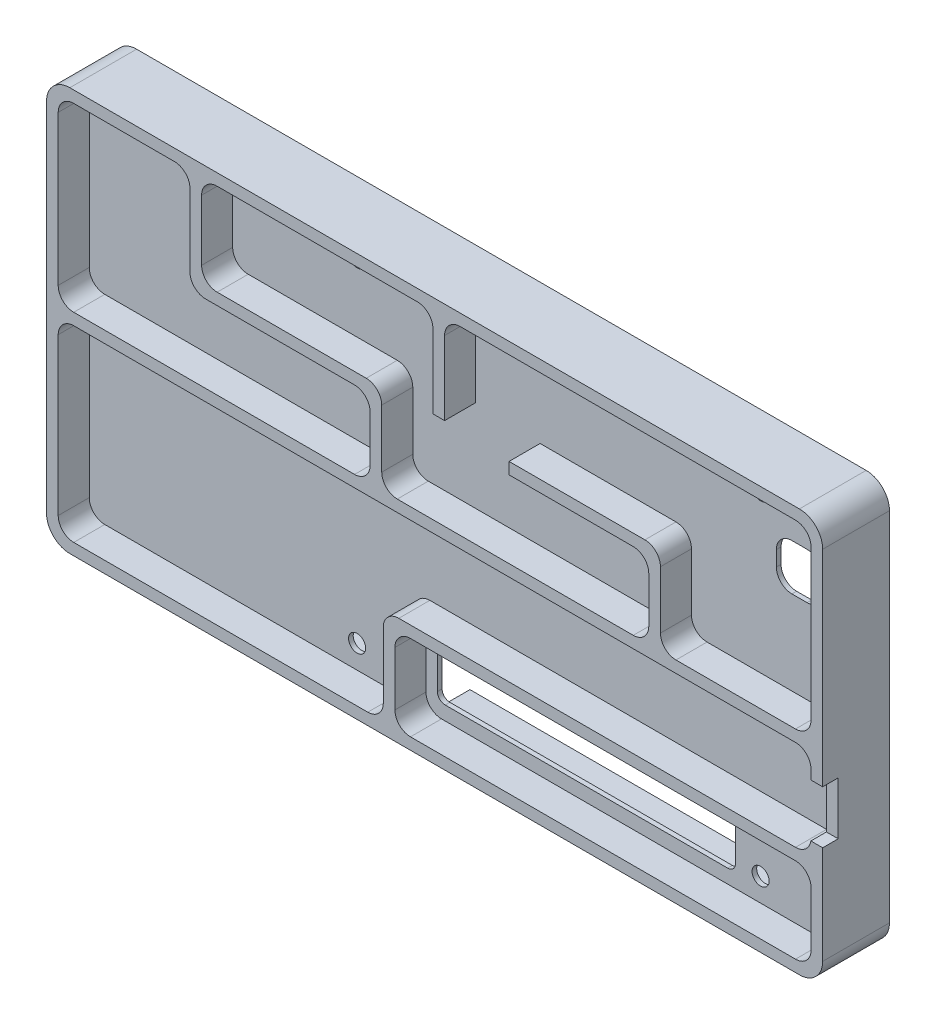
SolidWorks part; units mm, degrees
ref_plane "Front Plane" through (0, 0, 0) normal (0, 0, 1) x (1, 0, 0)
ref_plane "Top Plane" through (0, 0, 0) normal (0, 1, 0) x (1, 0, 0)
ref_plane "Right Plane" through (0, 0, 0) normal (1, 0, 0) x (0, 0, -1)
other "Configuration Table"
sketch "草图1" plane through (0, 0, 1046.4833) normal (0, 0, 1) x (1, 0, 0)
  line L0 (887.3759, 1046.1318) -> (981.3761, 1046.1318) construction
  line L1 (884.3886, 1046.1318) -> (984.3634, 1046.1318)
  line L2 (884.3886, 1046.1318) -> (884.3886, 994.1571)
  line L3 (884.3886, 994.1571) -> (984.3634, 994.1571)
  line L4 (984.3634, 1046.1318) -> (984.3634, 994.1571)
  line L6 (884.3886, 997.1444) -> (884.3886, 1043.1445) construction
  line L7 (984.3634, 1043.1445) -> (984.3634, 997.1444) construction
  line L8 (981.3761, 994.1571) -> (887.3759, 994.1571) construction
extrude "凸台-拉伸1" add sketch "草图1" along normal blind 8.6
sketch "草图2" plane through (0, 0, 1046.4833) normal (0, 0, -1) x (-1, 0, 0)
  line L0 (-884.3886, 1046.1318) -> (-884.3886, 994.1571) construction
  line L1 (-982.3634, 1044.1318) -> (-886.3886, 1044.1318)
  line L2 (-982.3634, 1044.1318) -> (-982.3634, 996.1571)
  line L3 (-982.3634, 996.1571) -> (-886.3886, 996.1571)
  line L4 (-886.3886, 1044.1318) -> (-886.3886, 996.1571)
  line L5 (-984.3634, 1046.1318) -> (-884.3886, 1046.1318) construction
  line L6 (-884.3886, 994.1571) -> (-984.3634, 994.1571) construction
  line L7 (-984.3634, 994.1571) -> (-984.3634, 1046.1318) construction
  dimension "D1" = 2
  dimension "D2" = 2
  dimension "D3" = 2
  dimension "D4" = 2
extrude "切除-拉伸1" cut sketch "草图2" against normal blind 4
sketch "草图3" plane through (0, 0, 1046.4833) normal (0, 0, -1) x (-1, 0, 0)
  line L0 (-886.3886, 996.1571) -> (-886.3886, 1044.1318) construction
  line L1 (-886.3886, 1039.1318) -> (-884.3886, 1039.1318)
  line L2 (-886.3886, 1039.1318) -> (-886.3886, 1029.1318)
  line L3 (-886.3886, 1029.1318) -> (-884.3886, 1029.1318)
  line L4 (-884.3886, 1039.1318) -> (-884.3886, 1029.1318)
  line L5 (-884.3886, 1046.1318) -> (-884.3886, 994.1571) construction
  line L8 (-984.3634, 1046.1318) -> (-884.3886, 1046.1318) construction
  line L9 (-886.3886, 1025.1318) -> (-884.3886, 1025.1318)
  line L10 (-886.3886, 1025.1318) -> (-886.3886, 1015.1571)
  line L11 (-886.3886, 1015.1571) -> (-884.3886, 1015.1571)
  line L12 (-884.3886, 1025.1318) -> (-884.3886, 1015.1571)
  line L13 (-886.3886, 1011.1571) -> (-884.3886, 1011.1571)
  line L14 (-886.3886, 1011.1571) -> (-886.3886, 1001.1571)
  line L15 (-886.3886, 1001.1571) -> (-884.3886, 1001.1571)
  line L16 (-884.3886, 1011.1571) -> (-884.3886, 1001.1571)
  line L17 (-884.3886, 994.1571) -> (-984.3634, 994.1571) construction
  dimension "D1" = 7
  dimension "D2" = 7
  dimension "D3" = 17
  dimension "D4" = 17
  dimension "D5" = 21
  dimension "D6" = 21
extrude "切除-拉伸2" cut sketch "草图3" against normal blind 3.35
sketch "草图4" plane through (0, 0, 1050.4833) normal (0, 0, -1) x (-1, 0, 0)
  line L0 (-984.3634, 1046.1318) -> (-884.3886, 1046.1318) construction
  line L1 (-969.1301, 1004.8444) -> (-930.7375, 1004.8444)
  line L2 (-969.1301, 1004.8444) -> (-969.1301, 997.4444)
  line L3 (-969.1301, 997.4444) -> (-930.7375, 997.4444)
  line L4 (-930.7375, 1004.8444) -> (-930.7375, 997.4444)
  line L5 (-980.351, 1038.1195) -> (-974.401, 1038.1195)
  line L6 (-980.351, 1038.1195) -> (-980.351, 1032.1695)
  line L7 (-980.351, 1032.1695) -> (-974.401, 1032.1695)
  line L8 (-974.401, 1038.1195) -> (-974.401, 1032.1695)
  line L9 (-984.3634, 994.1571) -> (-984.3634, 1046.1318) construction
  line L10 (-884.3886, 1046.1318) -> (-884.3886, 1039.1318) construction
  line L11 (-884.3886, 1001.1571) -> (-884.3886, 994.1571) construction
  line L12 (-884.3886, 994.1571) -> (-984.3634, 994.1571) construction
  circle A0 centre (-920.3886, 1041.6318) radius 1.1
  circle A1 centre (-920.3886, 998.6571) radius 1.1
  circle A2 centre (-972.3634, 998.6571) radius 1.1
  circle A3 centre (-972.3634, 1041.6318) radius 1.1
  dimension "D1" = 4.5
  dimension "D2" = 12
  dimension "D3" = 4.5
  dimension "D4" = 36
  dimension "D5" = 36
  dimension "D6" = 4.5
  dimension "D7" = 4.5
  dimension "D8" = 12
extrude "切除-拉伸3" cut sketch "草图4" against normal through all
sketch "草图6" plane through (0, 0, 1046.4833) normal (0, 0, -1) x (-1, 0, 0)
  line L1 (-930.3263, 1000.9528) -> (-923.5663, 1000.9528)
  line L2 (-930.3263, 1000.9528) -> (-930.3263, 994.1571)
  line L3 (-930.3263, 994.1571) -> (-923.5663, 994.1571)
  line L4 (-923.5663, 1000.9528) -> (-923.5663, 994.1571)
  line L5 (-884.3886, 994.1571) -> (-984.3634, 994.1571) construction
  line L6 (-929.8263, 995.0827) -> (-929.8263, 1000.0827) construction
  line L7 (-924.0663, 995.0827) -> (-924.0663, 1000.0827) construction
  dimension "D1" = 0.5
  dimension "D2" = 0.5
extrude "切除-拉伸4" cut sketch "草图6" against normal blind 4.5
sketch "草图7" plane through (0, 0, 1055.0833) normal (0, 0, 1) x (1, 0, 0)
  line L0 (984.3634, 994.1571) -> (984.3634, 1046.1318) construction
  line L5 (984.3634, 1046.1318) -> (884.3886, 1046.1318) construction
  line L11 (885.8886, 1019.8318) -> (982.8634, 1019.8318)
  line L13 (982.8634, 1008.1318) -> (927.7634, 1008.1318)
  line L30 (934.1634, 1044.6318) -> (934.1634, 1033.1318)
  line L31 (934.1634, 1033.1318) -> (935.6634, 1033.1318)
  line L32 (935.6634, 1044.6318) -> (935.6634, 1033.1318)
  line L36 (927.7634, 1008.1318) -> (927.7634, 1006.6318)
  line L42 (927.7634, 1006.6318) -> (927.7634, 995.6571)
  line L44 (929.2634, 1006.6318) -> (929.2634, 995.6571)
  line L45 (929.2634, 1006.6318) -> (982.8634, 1006.6318)
  line L46 (961.9634, 1021.3318) -> (961.9634, 1031.2318)
  line L47 (961.9634, 1031.2318) -> (943.9634, 1031.2318)
  line L48 (943.9634, 1031.2318) -> (943.9634, 1032.7318)
  line L49 (943.9634, 1032.7318) -> (963.4634, 1032.7318)
  line L50 (963.4634, 1032.7318) -> (963.4634, 1021.3318)
  line L51 (982.8634, 1021.3318) -> (963.4634, 1021.3318)
  line L53 (926.0634, 1021.3318) -> (926.0634, 1031.3118)
  line L56 (902.8634, 1031.3118) -> (902.8634, 1044.6318)
  line L58 (904.3634, 1044.6318) -> (904.3634, 1032.8118)
  line L59 (904.3634, 1032.8118) -> (927.5634, 1032.8118)
  line L60 (927.5634, 1032.8118) -> (927.5634, 1021.3318)
  line L61 (961.9634, 1021.3318) -> (927.5634, 1021.3318)
  line L62 (926.0634, 1021.3318) -> (885.8886, 1021.3318)
  line L64 (926.0634, 1031.3118) -> (902.8634, 1031.3118)
  line L65 (982.8634, 1021.3318) -> (982.8634, 1044.6318)
  line L66 (982.8634, 1044.6318) -> (935.6634, 1044.6318)
  line L67 (904.3634, 1044.6318) -> (934.1634, 1044.6318)
  line L68 (885.8886, 1044.6318) -> (885.8886, 1021.3318)
  line L70 (902.8634, 1044.6318) -> (885.8886, 1044.6318)
  line L71 (982.8634, 1008.1318) -> (982.8634, 1019.8318)
  line L72 (885.8886, 1019.8318) -> (885.8886, 995.6571)
  line L73 (885.8886, 995.6571) -> (927.7634, 995.6571)
  line L74 (929.2634, 995.6571) -> (982.8634, 995.6571)
  line L75 (982.8634, 1006.6318) -> (982.8634, 995.6571)
  dimension "D2" = 1.5
  dimension "D3" = 20.9
  dimension "D4" = 13.4
  dimension "D5" = 1.5
  dimension "D6" = 1.5
  dimension "D7" = 38
  dimension "D8" = 56.6
  dimension "D11" = 1.5
  dimension "D12" = 19.5
  dimension "D14" = 56.8
  dimension "D15" = 26.3
  dimension "D16" = 48.7
  dimension "D17" = 13
  dimension "D18" = 1.5
  dimension "D19" = 1.5
  dimension "D20" = 1.5
  dimension "D22" = 14.82
  dimension "D23" = 1.5
  dimension "D24" = 81.5
  dimension "D25" = 1.5
fillet "圆角1" radius 3 4 edges at (984.3634, 1046.1318, 1050.7833) (884.3886, 1046.1318, 1050.7833) (884.3886, 994.1571, 1050.7833) (984.3634, 994.1571, 1050.7833)
fillet "圆角3" radius 2 4 edges at (974.401, 1038.1195, 1052.7833) (974.401, 1032.1695, 1052.7833) (980.351, 1032.1695, 1052.7833) (980.351, 1038.1195, 1052.7833)
sketch "草图12" plane through (0, 0, 1050.4833) normal (0, 0, -1) x (-1, 0, 0)
  line L1 (-959.8699, 1027.3424) -> (-950.8699, 1027.3424)
  line L2 (-959.8699, 1027.3424) -> (-959.8699, 1018.3424)
  line L3 (-959.8699, 1018.3424) -> (-950.8699, 1018.3424)
  line L4 (-950.8699, 1027.3424) -> (-950.8699, 1018.3424)
  point P4 (-959.8699, 1027.3424)
  point P6 (-950.8699, 1018.3424)
  point P8 (-950.8699, 1018.3424)
extrude "凸台-拉伸3" add sketch "草图12" along normal blind 2.7
sketch "草图13" plane through (0, 0, 1050.4833) normal (0, 0, -1) x (-1, 0, 0)
  line L1 (-944.4751, 1027.3019) -> (-927.483, 1027.3019)
  line L2 (-944.4751, 1027.3019) -> (-944.4751, 1010.2546)
  line L3 (-944.4751, 1010.2546) -> (-927.483, 1010.2546)
  line L4 (-927.483, 1027.3019) -> (-927.483, 1010.2546)
extrude "凸台-拉伸4" add sketch "草图13" along normal blind 1.9
extrude "切除-拉伸14" cut sketch "草图7" against normal blind 4
fillet "圆角7" radius 2 34 edges at (885.8886, 995.6571, 1053.0833) (982.8634, 995.6571, 1053.0833) (927.7634, 995.6571, 1053.0833) (927.7634, 1008.1318, 1053.0833) (982.8634, 1008.1318, 1053.0833) (982.8634, 1006.6318, 1053.0833) (982.8634, 1019.8318, 1053.0833) (885.8886, 1019.8318, 1053.0833) (982.8634, 1021.3318, 1053.0833) (982.8634, 1044.6318, 1053.0833) (963.4634, 1021.3318, 1053.0833) (963.4634, 1032.7318, 1053.0833) (961.9634, 1031.2318, 1053.0833) (961.9634, 1021.3318, 1053.0833) (927.5634, 1021.3318, 1053.0833) (935.6634, 1044.6318, 1053.0833) (904.3634, 1044.6318, 1053.0833) (904.3634, 1032.8118, 1053.0833) (927.5634, 1032.8118, 1053.0833) (885.8886, 1021.3318, 1053.0833) (926.0634, 1021.3318, 1053.0833) (934.1634, 1044.6318, 1053.0833) (926.0634, 1031.3118, 1053.0833) (902.8634, 1031.3118, 1053.0833) (902.8634, 1044.6318, 1053.0833) (885.8886, 1044.6318, 1053.0833) (923.5663, 1000.9528, 1050.7333) (930.3263, 1000.9528, 1050.7333) (886.3886, 996.1571, 1048.4833) (886.3886, 1044.1318, 1048.4833) (982.3634, 996.1571, 1048.4833) (982.3634, 1044.1318, 1048.4833) (929.2634, 995.6571, 1053.0833) (929.2634, 1006.6318, 1053.0833)
fillet "圆角8" radius 1 4 edges at (930.7375, 997.4444, 1050.7833) (930.7375, 1004.8444, 1050.7833) (969.1301, 997.4444, 1050.7833) (969.1301, 1004.8444, 1050.7833)
sketch "草图14" plane through (0, 0, 1055.0833) normal (0, 0, 1) x (1, 0, 0)
  line L1 (982.0396, 1016.6318) -> (984.3634, 1016.6318)
  line L2 (982.0396, 1016.6318) -> (982.0396, 1009.8318)
  line L3 (982.0396, 1009.8318) -> (984.3634, 1009.8318)
  line L4 (984.3634, 1016.6318) -> (984.3634, 1009.8318)
  line L5 (981.3634, 1046.1318) -> (887.3886, 1046.1318) construction
  line L7 (984.3634, 997.1571) -> (984.3634, 1043.1318) construction
  dimension "D1" = 29.5
  dimension "D2" = 36.3
extrude "切除-拉伸15" cut sketch "草图14" against normal blind 2
